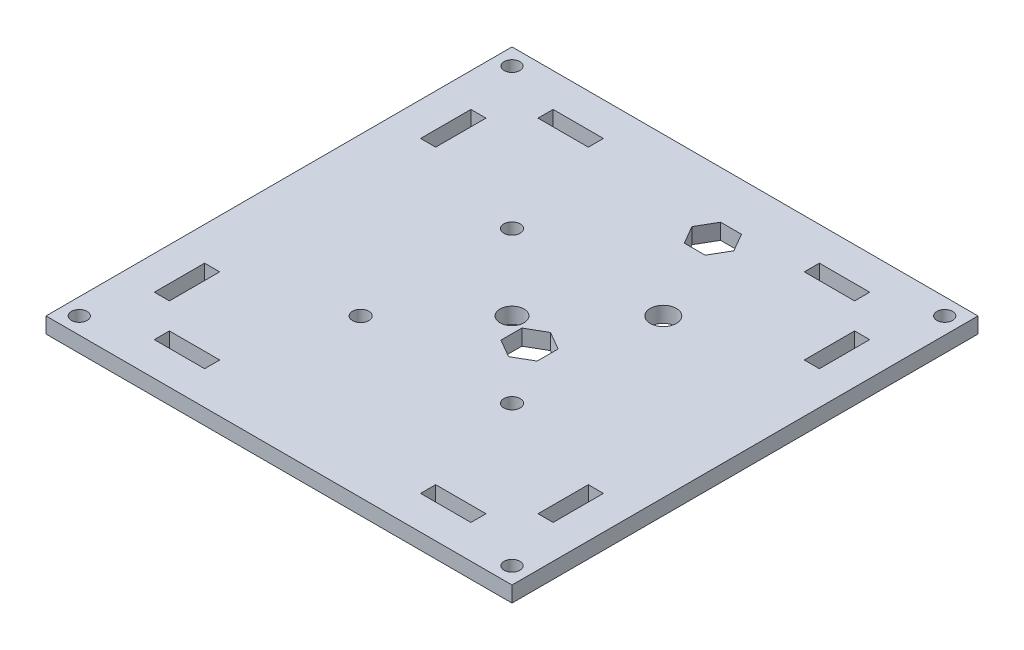
SolidWorks part; units mm, degrees
material "Acrylic (Medium-high impact)"
ref_plane "Front Plane" through (0, 0, 0) normal (0, 0, 1) x (1, 0, 0)
ref_plane "Top Plane" through (0, 0, 0) normal (0, 1, 0) x (1, 0, 0)
ref_plane "Right Plane" through (0, 0, 0) normal (1, 0, 0) x (0, 0, -1)
sketch "스케치2" plane through (0, 0, 0) normal (0, 0, 1) x (1, 0, 0)
  line L0 (44.45, -1.5) -> (46.85, 0.3) construction
  line L1 (-44.45, 1.5) -> (44.45, 1.5)
  line L2 (-44.45, 1.5) -> (-44.45, -1.5)
  line L3 (-44.45, -1.5) -> (44.45, -1.5)
  line L4 (44.45, 1.5) -> (44.45, -1.5) construction
  line L5 (-44.45, 1.5) -> (44.45, -1.5) construction
  line L6 (-44.45, -1.5) -> (44.45, 1.5) construction
  line L7 (44.45, -1.5) -> (62.738, -25.884) construction
  line L8 (46.85, 0.3) -> (65.138, -24.084) construction
  line L9 (62.738, -25.884) -> (65.138, -24.084) construction
  line L10 (44.45, -1.5) -> (44.45, -25.884) construction
  line L11 (44.45, -25.884) -> (62.738, -25.884) construction
  line L12 (44.45, 1.5) -> (44.45, -1.5)
  arc A0 (44.45, 1.5) -> (46.85, 0.3) centre (44.45, -1.5) cw construction
  point P0 (0, 0)
  dimension "D1" = 3
  dimension "D2" = 88.9
  dimension "D3" = 30.48
  dimension "D4" = 3
  dimension "D5" = 27.384
extrude "보스-돌출1" add sketch "스케치2" along normal blind 88.9 contours A0 L1 L2 L3 L7 L9 L8
sketch "스케치4" plane through (0, 1.5, 0) normal (0, 1, 0) x (1, 0, 0)
  line L0 (-44.45, -88.9) -> (-44.45, 0) construction
  line L1 (-44.45, -88.9) -> (44.45, -88.9) construction
  line L2 (-44.45, -88.9) -> (-44.45, 0) construction
  line L3 (-44.45, 0) -> (44.45, 0) construction
  line L4 (44.45, -88.9) -> (44.45, 0) construction
  line L5 (-44.45, -88.9) -> (44.45, 0) construction
  line L6 (-44.45, 0) -> (44.45, -88.9) construction
  line L7 (-44.45, 0) -> (44.45, 0) construction
  line L8 (-38.1, -82.55) -> (-44.45, -88.9) construction
  line L9 (-38.1, -82.55) -> (38.1, -82.55) construction
  line L10 (-38.1, -82.55) -> (-38.1, -6.35) construction
  line L11 (-38.1, -6.35) -> (38.1, -6.35) construction
  line L12 (38.1, -82.55) -> (38.1, -6.35) construction
  line L13 (-38.1, -82.55) -> (38.1, -6.35) construction
  line L14 (-38.1, -6.35) -> (38.1, -82.55) construction
  line L15 (44.45, 0) -> (38.1, -6.35) construction
  line L16 (0, -44.45) -> (0, -81.05) construction
  line L17 (-15.875, -79.55) -> (15.875, -79.55) construction
  line L18 (-15.875, -79.55) -> (-15.875, -82.55) construction
  line L19 (-15.875, -82.55) -> (15.875, -82.55) construction
  line L20 (15.875, -79.55) -> (15.875, -82.55) construction
  line L21 (-15.875, -79.55) -> (15.875, -82.55) construction
  line L22 (-15.875, -82.55) -> (15.875, -79.55) construction
  line L23 (-35.1, -28.575) -> (-38.1, -28.575) construction
  line L24 (-35.1, -28.575) -> (-35.1, -60.325) construction
  line L25 (-35.1, -60.325) -> (-38.1, -60.325) construction
  line L26 (-38.1, -28.575) -> (-38.1, -60.325) construction
  line L27 (15.875, -9.35) -> (15.875, -6.35) construction
  line L28 (15.875, -9.35) -> (-15.875, -9.35) construction
  line L29 (-15.875, -9.35) -> (-15.875, -6.35) construction
  line L30 (15.875, -6.35) -> (-15.875, -6.35) construction
  line L31 (35.1, -60.325) -> (38.1, -60.325) construction
  line L32 (35.1, -60.325) -> (35.1, -28.575) construction
  line L33 (35.1, -28.575) -> (38.1, -28.575) construction
  line L34 (38.1, -60.325) -> (38.1, -28.575) construction
  line L35 (0, -9.35) -> (0, -44.45) construction
  line L36 (-44.45, -88.9) -> (44.45, -88.9) construction
  line L37 (0, -44.45) -> (-35.1, -44.45) construction
  line L38 (35.1, -44.45) -> (0, -44.45) construction
  line L39 (-38.1, -65.05) -> (-35.1, -65.05) construction
  line L40 (-38.1, -14.25) -> (-35.1, -14.25) construction
  line L41 (-38.1, -14.25) -> (-38.1, -23.85) construction
  line L42 (-38.1, -23.85) -> (-35.1, -23.85) construction
  line L43 (-35.1, -14.25) -> (-35.1, -23.85) construction
  line L44 (-38.1, -14.25) -> (-35.1, -23.85) construction
  line L45 (-38.1, -23.85) -> (-35.1, -14.25) construction
  line L46 (-35.1, -74.65) -> (-35.1, -65.05) construction
  line L47 (-38.1, -74.65) -> (-35.1, -74.65) construction
  line L48 (-38.1, -74.65) -> (-38.1, -65.05) construction
  line L49 (38.1, -74.65) -> (38.1, -65.05) construction
  line L50 (38.1, -74.65) -> (35.1, -74.65) construction
  line L51 (35.1, -74.65) -> (35.1, -65.05) construction
  line L52 (38.1, -65.05) -> (35.1, -65.05) construction
  line L53 (38.1, -23.85) -> (35.1, -23.85) construction
  line L54 (35.1, -14.25) -> (35.1, -23.85) construction
  line L55 (38.1, -14.25) -> (35.1, -14.25) construction
  line L56 (38.1, -14.25) -> (38.1, -23.85) construction
  line L57 (30.2, -6.35) -> (20.6, -6.35) construction
  line L58 (-30.2, -9.35) -> (-20.6, -9.35) construction
  line L59 (-30.2, -9.35) -> (-30.2, -6.35) construction
  line L60 (-30.2, -6.35) -> (-20.6, -6.35) construction
  line L61 (-20.6, -9.35) -> (-20.6, -6.35) construction
  line L62 (-30.2, -9.35) -> (-20.6, -6.35) construction
  line L63 (-30.2, -6.35) -> (-20.6, -9.35) construction
  line L64 (20.6, -9.35) -> (20.6, -6.35) construction
  line L65 (30.2, -9.35) -> (20.6, -9.35) construction
  line L66 (30.2, -9.35) -> (30.2, -6.35) construction
  line L67 (30.2, -79.55) -> (30.2, -82.55) construction
  line L68 (30.2, -79.55) -> (20.6, -79.55) construction
  line L69 (20.6, -79.55) -> (20.6, -82.55) construction
  line L70 (30.2, -82.55) -> (20.6, -82.55) construction
  line L71 (-30.2, -82.55) -> (-20.6, -82.55) construction
  line L72 (-20.6, -79.55) -> (-20.6, -82.55) construction
  line L73 (-30.2, -79.55) -> (-20.6, -79.55) construction
  line L74 (-30.2, -79.55) -> (-30.2, -82.55) construction
  line L75 (-38.04, -74.65) -> (-35.16, -74.65)
  line L76 (-38.04, -23.85) -> (-35.16, -23.85)
  line L77 (-38.04, -23.85) -> (-38.04, -14.25)
  line L78 (-38.04, -14.25) -> (-35.16, -14.25)
  line L79 (-35.16, -23.85) -> (-35.16, -14.25)
  line L80 (-38.04, -23.85) -> (-35.16, -14.25) construction
  line L81 (-38.04, -14.25) -> (-35.16, -23.85) construction
  line L82 (-30.2, -6.41) -> (-20.6, -6.41)
  line L83 (-30.2, -6.41) -> (-30.2, -9.29)
  line L84 (-30.2, -9.29) -> (-20.6, -9.29)
  line L85 (-20.6, -6.41) -> (-20.6, -9.29)
  line L86 (-30.2, -6.41) -> (-20.6, -9.29) construction
  line L87 (-30.2, -9.29) -> (-20.6, -6.41) construction
  line L88 (-35.16, -65.05) -> (-35.16, -74.65)
  line L89 (-38.04, -65.05) -> (-35.16, -65.05)
  line L90 (-38.04, -65.05) -> (-38.04, -74.65)
  line L91 (38.04, -65.05) -> (38.04, -74.65)
  line L92 (38.04, -65.05) -> (35.16, -65.05)
  line L93 (35.16, -65.05) -> (35.16, -74.65)
  line L94 (38.04, -74.65) -> (35.16, -74.65)
  line L95 (38.04, -14.25) -> (35.16, -14.25)
  line L96 (35.16, -23.85) -> (35.16, -14.25)
  line L97 (38.04, -23.85) -> (35.16, -23.85)
  line L98 (38.04, -23.85) -> (38.04, -14.25)
  line L99 (30.2, -9.29) -> (20.6, -9.29)
  line L100 (20.6, -6.41) -> (20.6, -9.29)
  line L101 (30.2, -6.41) -> (20.6, -6.41)
  line L102 (30.2, -6.41) -> (30.2, -9.29)
  line L103 (30.2, -82.49) -> (30.2, -79.61)
  line L104 (30.2, -82.49) -> (20.6, -82.49)
  line L105 (20.6, -82.49) -> (20.6, -79.61)
  line L106 (30.2, -79.61) -> (20.6, -79.61)
  line L107 (-30.2, -79.61) -> (-20.6, -79.61)
  line L108 (-20.6, -82.49) -> (-20.6, -79.61)
  line L109 (-30.2, -82.49) -> (-20.6, -82.49)
  line L110 (-30.2, -82.49) -> (-30.2, -79.61)
  circle A0 centre (-41.275, -85.725) radius 1.5
  circle A1 centre (-41.275, -3.175) radius 1.5
  circle A2 centre (41.275, -3.175) radius 1.5
  circle A3 centre (41.275, -85.725) radius 1.5
  point P0 (0, -44.45)
  point P13 (0, -44.45)
  point P19 (0, -81.05)
  point P27 (0, -44.45)
  point P47 (0, -44.45)
  point P49 (-36.6, -19.05)
  point P65 (-25.4, -7.85)
  point P82 (-36.6, -19.05)
  point P87 (-25.4, -7.85)
  dimension "D3" = 3
  dimension "D1" = 76.2
  dimension "D2" = 76.2
  dimension "D5" = 3
  dimension "D6" = 31.75
  dimension "D8" = 35.1
  dimension "D7" = 88.9
  dimension "D9" = 3
  dimension "D10" = 35.1
  dimension "D11" = 35.1
  dimension "D12" = 9.6
  dimension "D13" = 25.4
  dimension "D14" = 3
  dimension "D15" = 9.6
  dimension "D16" = 3
  dimension "D17" = 25.4
  dimension "D18" = 2.88
  dimension "D19" = 2.88
  dimension "D4" = 4
extrude "컷-돌출1" cut sketch "스케치4" against normal up to surface (3 mm away) up to face at (0, -1.5, 44.45)
sketch "스케치5" plane through (0, 1.5, 0) normal (0, 1, 0) x (1, 0, 0)
  line L0 (0, 0) -> (0, -88.9) construction
  line L1 (-44.45, -88.9) -> (44.45, -88.9) construction
  line L2 (-44.45, -44.45) -> (44.45, -44.45) construction
  line L3 (-44.45, -88.9) -> (-44.45, 0) construction
  line L5 (44.45, -88.9) -> (44.45, 0) construction
  circle A0 centre (-14.4318, -30.0182) radius 15.875 construction
  circle A1 centre (-14.4318, -30.0182) radius 12.827 construction
  circle A2 centre (-14.4318, -30.0182) radius 1.56
  circle A3 centre (14.4318, -30.0182) radius 12.827 construction
  circle A4 centre (14.4318, -30.0182) radius 15.875 construction
  circle A5 centre (14.4318, -30.0182) radius 1.56
  circle A6 centre (14.4318, -58.8818) radius 12.827 construction
  circle A7 centre (14.4318, -58.8818) radius 15.875 construction
  circle A8 centre (14.4318, -58.8818) radius 1.56
  circle A9 centre (-14.4318, -58.8818) radius 12.827 construction
  circle A10 centre (-14.4318, -58.8818) radius 15.875 construction
  circle A11 centre (-14.4318, -58.8818) radius 1.56
  point P8 (0, -44.45)
  point P9 (-14.4318, -30.0182)
  point P10 (-1.6048, -30.0182)
  point P14 (-14.4318, -42.8452)
  point P34 (0, -44.45)
  dimension "D1" = 31.75
  dimension "D2" = 25.654
  dimension "D5" = 3.12
  dimension "D3" = 28.8636
  dimension "D4" = 28.8636
  dimension "D6" = 4
extrude "컷-돌출2" cut sketch "스케치5" against normal up to surface (3 mm away) up to face at (36.6, -1.5, 19.05)
sketch "스케치7" plane through (0, 1.5, 0) normal (0, 1, 0) x (1, 0, 0)
  line L0 (22.4618, -12.5282) -> (22.4618, -47.5082) construction
  line L1 (14.4318, -30.0182) -> (22.4618, -30.0182) construction
  line L2 (14.4318, -30.0182) -> (14.4318, -9.35) construction
  line L3 (26.4571, -12.5282) -> (24.4595, -9.0682) construction
  line L4 (24.4595, -9.0682) -> (20.4642, -9.0682) construction
  line L5 (20.4642, -9.0682) -> (18.4666, -12.5282) construction
  line L6 (18.4666, -12.5282) -> (20.4642, -15.9882) construction
  line L7 (20.4642, -15.9882) -> (24.4595, -15.9882) construction
  line L8 (24.4595, -15.9882) -> (26.4571, -12.5282) construction
  line L9 (25.9218, -49.5058) -> (25.9218, -45.5105) construction
  line L10 (25.9218, -45.5105) -> (22.4618, -43.5129) construction
  line L11 (22.4618, -43.5129) -> (19.0018, -45.5105) construction
  line L12 (19.0018, -45.5105) -> (19.0018, -49.5058) construction
  line L13 (19.0018, -49.5058) -> (22.4618, -51.5034) construction
  line L14 (22.4618, -51.5034) -> (25.9218, -49.5058) construction
  line L15 (-20.6, -9.35) -> (14.4318, -9.35) construction
  line L16 (6.4018, -51.5034) -> (2.9418, -49.5058)
  line L17 (9.8618, -49.5058) -> (6.4018, -51.5034)
  line L18 (9.8618, -45.5105) -> (9.8618, -49.5058)
  line L19 (6.4018, -43.5129) -> (9.8618, -45.5105)
  line L20 (2.9418, -45.5105) -> (6.4018, -43.5129)
  line L21 (2.9418, -49.5058) -> (2.9418, -45.5105)
  line L22 (4.4042, -15.9882) -> (2.4066, -12.5282)
  line L23 (8.3995, -15.9882) -> (4.4042, -15.9882)
  line L24 (10.3971, -12.5282) -> (8.3995, -15.9882)
  line L25 (8.3995, -9.0682) -> (10.3971, -12.5282)
  line L26 (4.4042, -9.0682) -> (8.3995, -9.0682)
  line L27 (2.4066, -12.5282) -> (4.4042, -9.0682)
  line L29 (-20.6, -9.29) -> (-20.6, -6.41) construction
  line L30 (-30.2, -9.35) -> (-20.6, -9.35) construction
  line L31 (-30.2, -9.35) -> (-30.2, -6.35) construction
  line L32 (-30.2, -6.35) -> (-20.6, -6.35) construction
  line L33 (-20.6, -9.35) -> (-20.6, -6.35) construction
  line L34 (-30.2, -9.35) -> (-20.6, -6.35) construction
  line L35 (-30.2, -6.35) -> (-20.6, -9.35) construction
  circle A0 centre (14.4318, -30.0182) radius 4.635 construction
  circle A1 centre (22.4618, -12.5282) radius 2.23 construction
  circle A2 centre (22.4618, -47.5082) radius 2.23 construction
  circle A3 centre (14.4318, -30.0182) radius 1.56 construction
  circle A4 centre (22.4618, -30.0182) radius 14.045 construction
  circle A6 centre (14.4318, -30.0182) radius 15.875 construction
  circle A7 centre (14.4318, -58.8818) radius 15.875 construction
  circle A8 centre (14.4318, -30.0182) radius 2.495
  circle A9 centre (22.4618, -12.5282) radius 3.46 construction
  circle A10 centre (22.4618, -47.5082) radius 3.46 construction
  circle A11 centre (6.4018, -12.5282) radius 3.46 construction
  point P7 (9.7968, -30.0182)
  point P8 (8.4168, -30.0182)
  point P32 (-25.4, -7.85)
  point P52 (-20.6, -7.85)
  point P53 (-20.6, -7.85)
  point P54 (-20.6, -7.85)
  dimension "D1" = 9.27
  dimension "D2" = 4.46
  dimension "D4" = 28.09
  dimension "D6" = 31.75
  dimension "D7" = 4.99
  dimension "D3" = 34.98
  dimension "D5" = 1.38
  dimension "D8" = 6.92
  dimension "D9" = 3
extrude "컷-돌출3" cut sketch "스케치7" against normal up to surface (3 mm away) up to face at (-14.4318, -1.5, 60.4418)
sketch "스케치8" plane through (0, 1.5, 0) normal (0, 1, 0) x (1, 0, 0)
  line L1 (44.45, -88.9) -> (-44.45, -88.9) construction
  line L2 (44.45, -88.9) -> (44.45, 0) construction
  line L3 (44.45, 0) -> (-44.45, 0) construction
  line L4 (-44.45, -88.9) -> (-44.45, 0) construction
  line L5 (44.45, -88.9) -> (-44.45, 0) construction
  line L6 (44.45, 0) -> (-44.45, -88.9) construction
  circle A0 centre (0, -44.45) radius 2.286
  point P0 (0, -44.45)
  dimension "D1" = 4.572
extrude "컷-돌출4" cut sketch "스케치8" against normal up to surface (3 mm away) up to face at (14.4318, -1.5, 32.5132)
